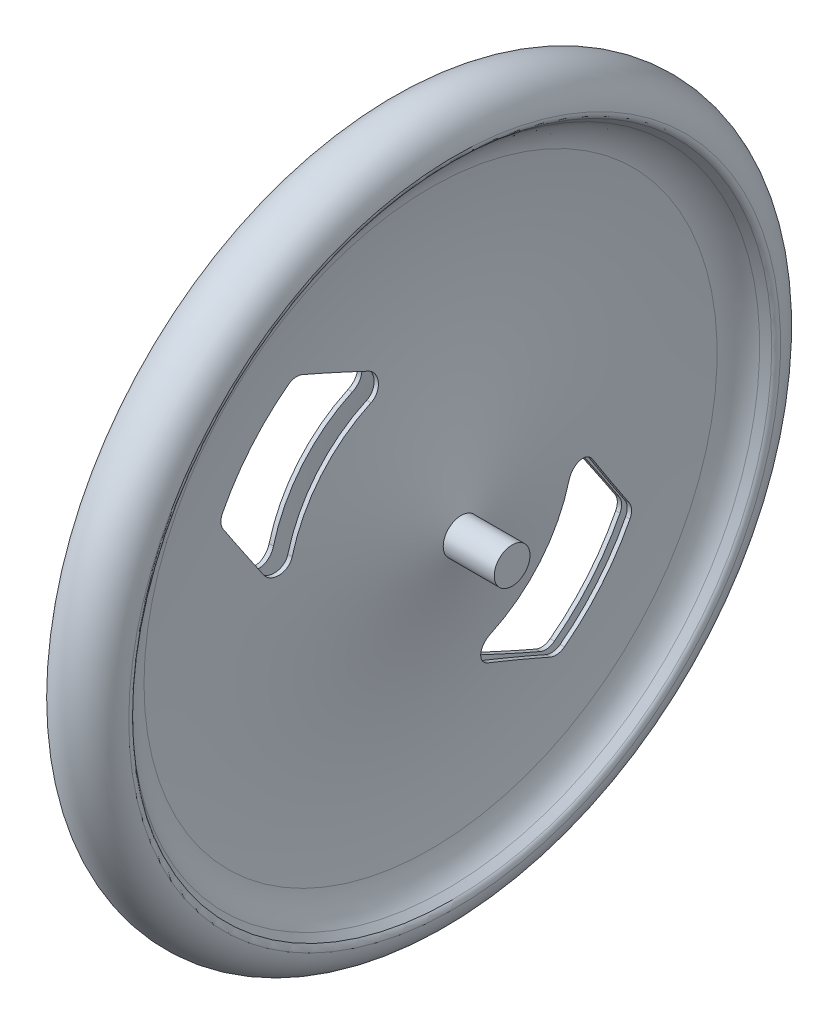
SolidWorks part; units mm, degrees
ref_plane "Front Plane" through (0, 0, 0) normal (0, 0, 1) x (1, 0, 0)
ref_plane "Top Plane" through (0, 0, 0) normal (0, 1, 0) x (1, 0, 0)
ref_plane "Right Plane" through (0, 0, 0) normal (1, 0, 0) x (0, 0, -1)
sketch "Sketch1" plane through (0, 0, 0) normal (0, 0, 1) x (1, 0, 0)
  line L0 (0, 0) -> (351.6274, 0) construction
  line L1 (0, 0) -> (0, 280.0063) construction
  line L2 (23.0895, 223.3969) -> (18.4882, 219.536)
  line L5 (-23.0895, 223.3969) -> (-18.4882, 219.536)
  line L6 (-29.3537, 12.5) -> (29.3537, 12.5)
  arc A0 (-24.8445, 227.784) -> (24.8445, 227.784) centre (0, 225) cw
  arc A1 (8.0072, 200.3052) -> (29.3537, 12.5) centre (404.869, 150.2979) ccw
  arc A2 (18.4882, 219.536) -> (8.0072, 200.3052) centre (37.7718, 196.5546) ccw
  arc A3 (24.8445, 227.784) -> (23.0895, 223.3969) centre (19.8756, 227.2272) cw
  arc A4 (-8.0072, 200.3052) -> (-29.3537, 12.5) centre (-404.869, 150.2979) cw
  arc A5 (-18.4882, 219.536) -> (-8.0072, 200.3052) centre (-37.7718, 196.5546) cw
  arc A6 (-24.8445, 227.784) -> (-23.0895, 223.3969) centre (-19.8756, 227.2272) ccw
  point P2 (0, 250)
  point P27 (9.6791, 212.1442)
  point P31 (25, 225)
  dimension "D2" = 25
  dimension "D6" = 400
  dimension "D7" = 30
  dimension "D8" = 5
  dimension "D1" = 25
  dimension "D3" = 250
  dimension "D4" = 50
  dimension "D5" = 20
revolve "Revolve1" add sketch "Sketch1" angle 360 about L0
shell "Shell2" thickness 3
sketch "Sketch2" plane through (0, 0, 0) normal (1, 0, 0) x (0, 0, -1)
  line L0 (-122.5671, 102.846) -> (-76.6044, 64.2788) construction
  line L1 (-114.7713, 22.1914) -> (-141.8299, 62.8425)
  line L4 (-86.5163, 128.7627) -> (-41.784, 109.1741)
  line L5 (0, 0) -> (-17.3648, 98.4808) construction
  line L6 (0, 0) -> (-100, 0) construction
  line L7 (0, 0) -> (-91.7722, 131.0643) construction
  line L8 (0, 0) -> (-145.0092, 67.6189) construction
  line L13 (86.5163, -128.7627) -> (41.784, -109.1741)
  line L14 (114.7713, -22.1914) -> (141.8299, -62.8425)
  arc A2 (-96.7698, 25.2113) -> (-41.6321, 90.9218) centre (0, 0) cw
  arc A3 (-142.4058, 72.9424) -> (-96.5628, 127.576) centre (0, 0) cw
  arc A4 (-41.6321, 90.9218) -> (-41.784, 109.1741) centre (-45.7954, 100.0139) ccw
  arc A5 (-96.7698, 25.2113) -> (-114.7713, 22.1914) centre (-106.4468, 27.7324) cw
  arc A6 (-96.5628, 127.576) -> (-86.5163, 128.7627) centre (-90.5276, 119.6025) cw
  arc A7 (-142.4058, 72.9424) -> (-141.8299, 62.8425) centre (-133.5054, 68.3835) ccw
  arc A20 (96.5628, -127.576) -> (86.5163, -128.7627) centre (90.5276, -119.6025) cw
  arc A21 (41.6321, -90.9218) -> (41.784, -109.1741) centre (45.7954, -100.0139) ccw
  arc A22 (96.7698, -25.2113) -> (41.6321, -90.9218) centre (0, 0) cw
  arc A23 (96.7698, -25.2113) -> (114.7713, -22.1914) centre (106.4468, -27.7324) cw
  arc A24 (142.4058, -72.9424) -> (141.8299, -62.8425) centre (133.5054, -68.3835) ccw
  arc A25 (142.4058, -72.9424) -> (96.5628, -127.576) centre (0, 0) cw
  point P34 (0, 0)
  point P35 (76.6044, -64.2788)
  point P46 (0, 0)
  dimension "D1" = 100
  dimension "D2" = 160
  dimension "D5" = 10
  dimension "D3" = 80
  dimension "D4" = 30
  dimension "D6" = 2
extrude "Cut-Extrude1" cut sketch "Sketch2" against normal up to surface and the other way up to surface up to face at (-29.3537, 0, 12.5) other way up to face at (8.0072, 0, 200.3052)
sketch "Sketch3" plane through (0, 0, 0) normal (1, 0, 0) x (0, 0, -1)
  circle A0 centre (0, 0) radius 12.5
  circle A1 centre (0, 0) radius 12.5 construction
extrude "Boss-Extrude1" add sketch "Sketch3" along normal mid plane 130
